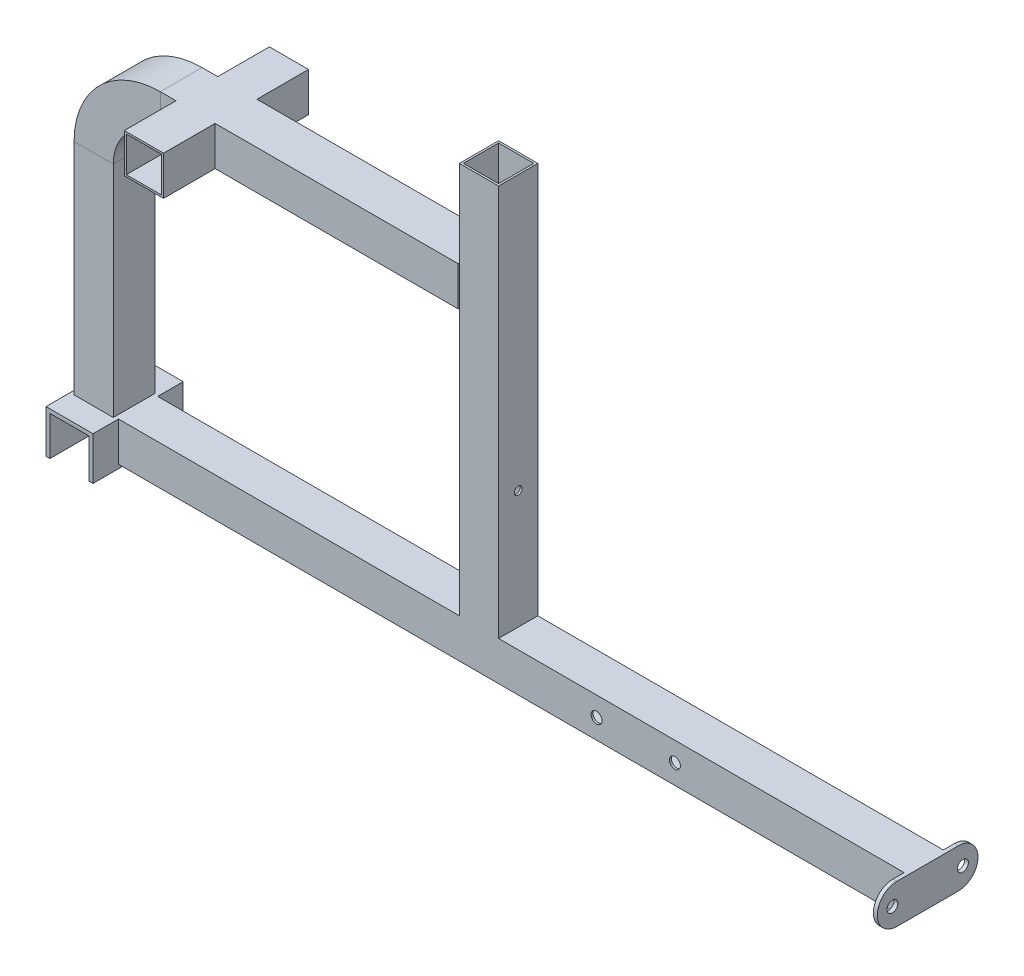
SolidWorks part; units mm, degrees
ref_plane "Front Plane" through (0, 0, 0) normal (0, 0, 1) x (1, 0, 0)
ref_plane "Top Plane" through (0, 0, 0) normal (0, 1, 0) x (1, 0, 0)
ref_plane "Right Plane" through (0, 0, 0) normal (1, 0, 0) x (0, 0, -1)
sketch "Sketch1" plane through (0, 0, 0) normal (0, 0, 1) x (1, 0, 0)
  line L0 (0, 0) -> (0, 280)
  line L1 (85, 365) -> (465, 365)
  arc A0 (0, 280) -> (85, 365) centre (85, 280) cw
  dimension "D2" = 85
  dimension "D1" = 280
  dimension "D3" = 465
sketch "Sketch3" plane through (0, 0, 0) normal (0, 1, 0) x (1, 0, 0)
  line L1 (25, -26.6823) -> (-25, -26.6823)
  line L2 (25, -26.6823) -> (25, 26.6823)
  line L3 (25, 26.6823) -> (-25, 26.6823)
  line L4 (-25, -26.6823) -> (-25, 26.6823)
  line L5 (25, -26.6823) -> (-25, 26.6823) construction
  line L6 (25, 26.6823) -> (-25, -26.6823) construction
  line L7 (22.5, -24.014) -> (-22.5, -24.014)
  line L8 (22.5, -24.014) -> (22.5, 24.014)
  line L9 (22.5, 24.014) -> (-22.5, 24.014)
  line L10 (-22.5, -24.014) -> (-22.5, 24.014)
  line L11 (22.5, -24.014) -> (-22.5, 24.014) construction
  line L12 (22.5, 24.014) -> (-22.5, -24.014) construction
  point P0 (0, 0)
  point P6 (0, 0)
  dimension "D1" = 50
  dimension "D2" = 45
sweep "Sweep1" add profiles "Sketch3" path "Sketch1"
ref_plane "Plane2" through (130, 0, 0) normal (1, 0, 0) x (0, 0, -1)
sketch "Sketch5" plane through (130, 0, 0) normal (1, 0, 0) x (0, 0, -1)
  line L0 (92.5, 365) -> (-92.5, 365)
  line L1 (-26.6823, 390) -> (-26.6823, 340) construction
  line L2 (26.6823, 340) -> (26.6823, 390) construction
  point P0 (0, 365)
  point P2 (-26.6823, 365)
  point P5 (0, 365)
  point P6 (26.6823, 365)
ref_plane "Plane3" through (0, 0, 25) normal (0, 0, 1) x (1, 0, 0)
ref_plane "Plane4" through (0, 0, -25) normal (0, 0, 1) x (1, 0, 0)
sketch "Sketch6" plane through (0, 0, -25) normal (0, 0, 1) x (1, 0, 0)
  line L0 (85, 390) -> (465, 390) construction
  line L1 (155, 340) -> (105, 340)
  line L2 (155, 340) -> (155, 390)
  line L3 (155, 390) -> (105, 390)
  line L4 (105, 340) -> (105, 390)
  line L5 (155, 340) -> (105, 390) construction
  line L6 (155, 390) -> (105, 340) construction
  line L8 (152.5, 342.5) -> (107.5, 342.5)
  line L9 (152.5, 342.5) -> (152.5, 387.5)
  line L10 (152.5, 387.5) -> (107.5, 387.5)
  line L11 (107.5, 342.5) -> (107.5, 387.5)
  line L12 (152.5, 342.5) -> (107.5, 387.5) construction
  line L13 (152.5, 387.5) -> (107.5, 342.5) construction
  point P0 (130, 365)
  point P2 (130, 365)
  point P9 (130, 365)
  dimension "D1" = 50
  dimension "D2" = 45
extrude "Boss-Extrude1" add sketch "Sketch6" against normal up to vertex (67.5 mm away) up to point (130, 365, -92.5)
mirror "Mirror1" about plane through (0, 0, 0) normal (0, 0, 1) of "Boss-Extrude1"
ref_plane "Plane5" through (490, 0, 0) normal (1, 0, 0) x (0, 0, -1)
sketch "Sketch7" plane through (490, 0, 0) normal (1, 0, 0) x (0, 0, -1)
  line L0 (0, 0) -> (0, 500)
  point P0 (0, 0)
  dimension "D1" = 500
sketch "Sketch8" plane through (0, 0, 0) normal (0, 1, 0) x (1, 0, 0)
  line L1 (465, -25) -> (515, -25)
  line L2 (465, -25) -> (465, 25)
  line L3 (465, 25) -> (515, 25)
  line L4 (515, -25) -> (515, 25)
  line L5 (465, -25) -> (515, 25) construction
  line L6 (465, 25) -> (515, -25) construction
  line L7 (467.5, -22.5) -> (512.5, -22.5)
  line L8 (467.5, -22.5) -> (467.5, 22.5)
  line L9 (467.5, 22.5) -> (512.5, 22.5)
  line L10 (512.5, -22.5) -> (512.5, 22.5)
  line L11 (467.5, -22.5) -> (512.5, 22.5) construction
  line L12 (467.5, 22.5) -> (512.5, -22.5) construction
  point P0 (490, 0)
  point P2 (490, 0)
  point P7 (490, 0)
  dimension "D1" = 50
  dimension "D2" = 50
  dimension "D3" = 45
extrude "Boss-Extrude2" add sketch "Sketch8" along normal up to vertex (500 mm away) up to point (490, 500, 0)
sketch "Sketch9" plane through (0, 0, 25) normal (0, 0, 1) x (1, 0, 0)
  line L1 (152.5, 342.5) -> (107.5, 342.5)
  line L2 (152.5, 342.5) -> (152.5, 387.5)
  line L3 (152.5, 387.5) -> (107.5, 387.5)
  line L4 (107.5, 342.5) -> (107.5, 387.5)
  line L5 (152.5, 342.5) -> (107.5, 387.5) construction
  line L6 (152.5, 387.5) -> (107.5, 342.5) construction
  point P0 (130, 365)
  point P2 (130, 365)
extrude "Cut-Extrude1" cut sketch "Sketch9" against normal through all both and the other way through all
ref_plane "Plane7" through (25, 0, 0) normal (1, 0, 0) x (0, 0, -1)
sketch "Sketch12" plane through (0, 0, 0) normal (0, 1, 0) x (1, 0, 0)
  line L0 (-22.5, -24.014) -> (-22.5, 24.014) construction
  line L1 (-30, -57.5) -> (30, -57.5)
  line L2 (-30, -57.5) -> (-30, 57.5)
  line L3 (-30, 57.5) -> (30, 57.5)
  line L4 (30, -57.5) -> (30, 57.5)
  line L5 (-30, -57.5) -> (30, 57.5) construction
  line L6 (-30, 57.5) -> (30, -57.5) construction
  line L7 (22.5, -24.014) -> (-22.5, -24.014) construction
  line L8 (22.5, 24.014) -> (22.5, -24.014) construction
  line L9 (-22.5, 24.014) -> (22.5, 24.014) construction
  line L10 (-22.5, -24.014) -> (-22.5, 24.014)
  line L11 (22.5, -24.014) -> (-22.5, -24.014)
  line L12 (22.5, 24.014) -> (22.5, -24.014)
  line L13 (-22.5, 24.014) -> (22.5, 24.014)
  point P0 (0, 0)
  dimension "D1" = 115
  dimension "D2" = 60
extrude "Boss-Extrude6" add sketch "Sketch12" against normal blind 5
ref_plane "Plane8" through (-25, 0, 0) normal (1, 0, 0) x (0, 0, -1)
sketch "Sketch14" plane through (-25, 0, 0) normal (1, 0, 0) x (0, 0, -1)
  line L0 (57.5, 0) -> (-57.5, 0) construction
  line L1 (57.5, 0) -> (-57.5, 0)
  line L3 (57.5, 0) -> (-57.5, 0)
  line L4 (57.5, 0) -> (57.5, -55)
  line L5 (57.5, -55) -> (-57.5, -55)
  line L6 (-57.5, 0) -> (-57.5, -55)
  dimension "D1" = 115
  dimension "D2" = 55
extrude "Boss-Extrude7" add sketch "Sketch14" against normal blind 5 contours L1 L6 L5 L4
mirror "Mirror2" about plane through (0, 0, 0) normal (1, 0, 0) of "Boss-Extrude7"
sketch "Sketch15" plane through (30, 0, 0) normal (1, 0, 0) x (0, 0, -1)
  line L2 (-25, 0) -> (-25, -50)
  line L3 (-25, -50) -> (25, -50)
  line L4 (25, 0) -> (25, -50)
  line L5 (-22.5, -2.8897) -> (-22.5, -47.8897)
  line L6 (-22.5, -47.8897) -> (22.5, -47.8897)
  line L7 (22.5, -47.8897) -> (22.5, -2.8897)
  line L8 (-22.5, -2.8897) -> (22.5, -2.8897)
  line L10 (-25, 0) -> (25, 0)
  line L11 (0, -1000) -> (0, 49000) construction
  dimension "D1" = 90
  dimension "D2" = 50
  dimension "D3" = 45
  dimension "D4" = 50
  dimension "D5" = 50
  dimension "D6" = 25
  dimension "D7" = 2.5
  dimension "D8" = 45
extrude "Boss-Extrude8" add sketch "Sketch15" along normal blind 1005
sketch "Sketch18" plane through (0, 0, 25) normal (0, 0, 1) x (1, 0, 0)
  line L2 (490, 0) -> (640, 0) construction
  line L3 (1035, 0) -> (515, 0) construction
  line L4 (640, 0) -> (640, -25) construction
  line L5 (490, 0) -> (740, 0) construction
  line L6 (740, 0) -> (740, -25) construction
  circle A0 centre (640, -25) radius 7
  circle A1 centre (740, -25) radius 7
  point P0 (490, 0)
  dimension "D3" = 14
  dimension "D5" = 14
  dimension "D1" = 100
  dimension "D2" = 25
  dimension "D4" = 25
extrude "Cut-Extrude3" cut sketch "Sketch18" along normal through all both and the other way through all contours A0 | A1
sketch "Sketch19" plane through (1035, 0, 0) normal (1, 0, 0) x (0, 0, -1)
  line L0 (25, 0) -> (-25, 0) construction
  line L1 (25, 0) -> (-25, 0)
  line L3 (-25, -50) -> (25, -50)
  line L4 (25, -50) -> (25, 0)
  line L5 (26.4202, 0) -> (26.6823, 0)
  line L6 (39.2797, -49.9331) -> (25, -50)
  line L7 (0, -24.9666) -> (45, -24.9666) construction
  line L8 (39.2797, 0) -> (26.6823, 0)
  line L9 (26.6823, 0) -> (25, 0)
  line L10 (0, -1024.9666) -> (0, 48975.0334) construction
  line L11 (-39.2797, -49.9331) -> (-25, -50)
  line L12 (-26.6823, 0) -> (-25, 0)
  line L13 (-39.2797, 0) -> (-26.6823, 0)
  arc A0 (39.2797, -49.9331) -> (39.2797, 0) centre (39.2797, -24.9666) ccw
  circle A1 centre (45, -24.9666) radius 7
  arc A2 (-39.2797, -49.9331) -> (-39.2797, 0) centre (-39.2797, -24.9666) cw
  circle A3 centre (-45, -24.9666) radius 7
  point P13 (0, -24.9666)
  line M1 (25, 0) -> (-25, 0)
  line M2 (-25, 0) -> (-25, -50)
  line M3 (-25, -50) -> (25, -50)
  line M4 (25, -50) -> (25, 0)
  line M5 (-22.5, -2.8897) -> (22.5, -2.8897)
  line M6 (22.5, -2.8897) -> (22.5, -47.8897)
  line M7 (22.5, -47.8897) -> (-22.5, -47.8897)
  line M8 (-22.5, -47.8897) -> (-22.5, -2.8897)
  dimension "D1" = 24.9666
  dimension "D2" = 14
  dimension "D3" = 90
extrude "Boss-Extrude9" add sketch "Sketch19" along normal mid plane 5 contours A3 L12 L13 A2 L11 M2 | A3 A1 M2 M3 M4 M1 M8 M5 M6 M7 | M5 M8 M7 M6 | A1 L6 A0 L8 L5 L9 M4
sketch "Sketch20" plane through (515, 0, 0) normal (1, 0, 0) x (0, 0, -1)
  circle A0 centre (0, 150.7487) radius 5
  dimension "D1" = 10
extrude "Cut-Extrude4" cut sketch "Sketch20" against normal up to surface (50 mm away) up to face at (465, 170, 0)
